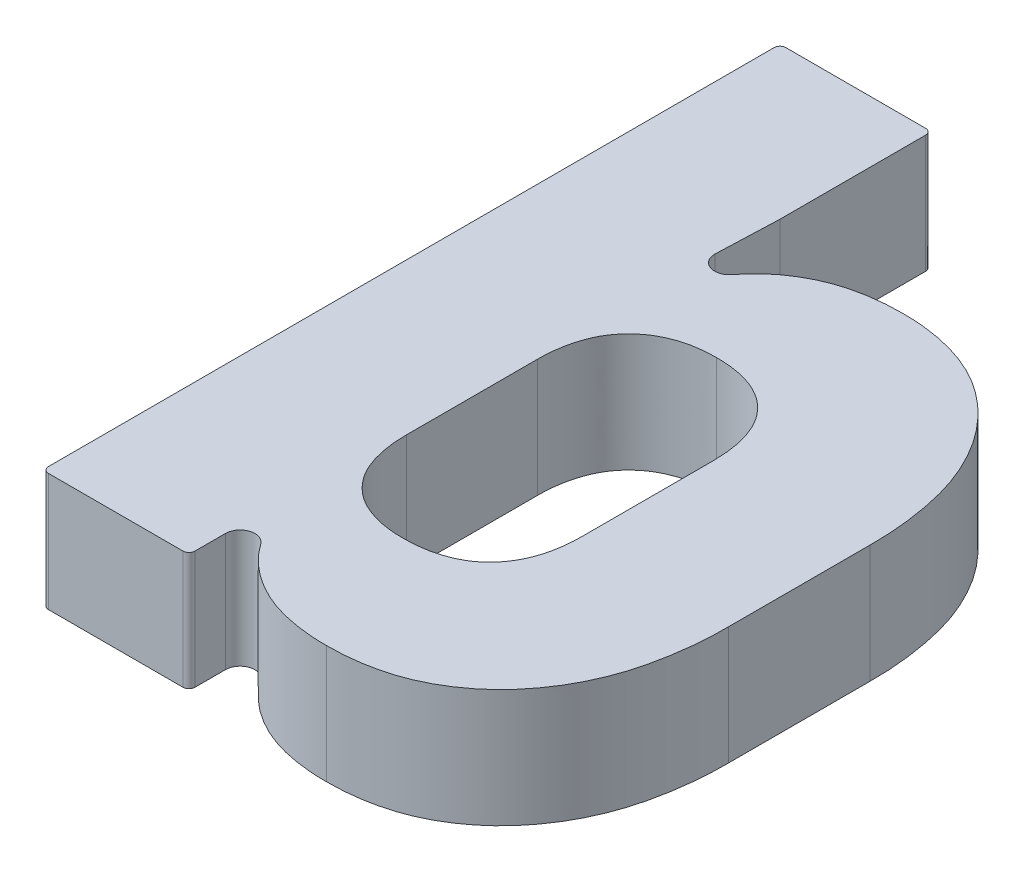
SolidWorks part; units mm, degrees
ref_plane "Front Plane" through (0, 0, 0) normal (0, 0, 1) x (1, 0, 0)
ref_plane "Top Plane" through (0, 0, 0) normal (0, 1, 0) x (1, 0, 0)
ref_plane "Right Plane" through (0, 0, 0) normal (1, 0, 0) x (0, 0, -1)
sketch "Sketch1" plane through (0, 0, 0) normal (0, 1, 0) x (1, 0, 0)
  line L2 (36.1177, 19.9168) -> (36.1177, 0)
  line L3 (36.1177, 0) -> (11.2961, 0)
  line L4 (11.2961, 0) -> (11.2961, 125)
  line L5 (11.2961, 125) -> (36.9847, 125)
  line L6 (36.9847, 125) -> (36.9847, 99.3113)
  line L7 (36.9847, 99.3113) -> (36.1177, 76.199)
  line L10 (92.4495, 59.0815) -> (92.4495, 35.1021)
  line L11 (66.7856, 35.9691) -> (66.7856, 58.2144)
  line L12 (36.9847, 58.2144) -> (36.9847, 35.9691)
  spline S0 degree 3 poles (61.1375, -1.7093) (59.2964, -1.7263) (56.5951, -1.5145) (53.1297, -0.8168) (50.743, -0.0788) (48.524, 0.8997) (46.4557, 2.0674) (44.5312, 3.4383) (42.7707, 5.0197) (41.2152, 6.8114) (39.8415, 8.7587) (38.6541, 10.872) (37.2413, 14.5656) (36.5093, 17.6313) (36.1177, 19.9168) knots 0 0 0 0 0.15065 0.22105 0.289042 0.354731 0.419211 0.48318 0.547799 0.612474 0.676994 0.742654 0.810317 1 1 1 1
  spline S1 degree 3 poles (36.1177, 76.199) (37.079, 78.5138) (37.8217, 81.825) (39.8413, 85.4251) (41.2153, 87.372) (42.7706, 89.1639) (44.5312, 90.7452) (46.4557, 92.1161) (48.524, 93.2838) (50.743, 94.2623) (53.1297, 95.0003) (56.5951, 95.698) (59.2964, 95.9098) (61.1375, 95.8928) knots 0 0 0 0 0.21768 0.286848 0.354813 0.422943 0.491013 0.558398 0.626323 0.69552 0.767144 0.841304 1 1 1 1
  spline S2 degree 3 poles (61.1375, 95.8928) (63.3951, 95.9037) (66.7358, 95.6213) (70.9813, 94.5442) (73.936, 93.4517) (76.7059, 92.0301) (79.2899, 90.2803) (81.7146, 88.2364) (83.9267, 85.8824) (85.9422, 83.2868) (87.6702, 80.4423) (89.1706, 77.4064) (90.3909, 74.1471) (91.2891, 70.6632) (92.1999, 65.6448) (92.4801, 61.7415) (92.4495, 59.0815) knots 0 0 0 0 0.124488 0.183663 0.240987 0.297785 0.354849 0.412665 0.472231 0.532595 0.593488 0.655373 0.719037 0.784951 0.85343 1 1 1 1
  spline S3 degree 3 poles (92.4495, 35.1021) (92.4817, 32.4172) (92.2002, 28.4812) (91.2918, 23.4291) (90.3921, 19.9366) (89.1629, 16.6738) (87.685, 13.6255) (85.9322, 10.7958) (83.9353, 8.2026) (81.7126, 5.8731) (79.2902, 3.8513) (76.6987, 2.131) (73.9363, 0.7078) (70.985, -0.3925) (66.7284, -1.416) (63.398, -1.7319) (61.1375, -1.7093) knots 0 0 0 0 0.147807 0.216676 0.282534 0.346145 0.408386 0.46884 0.529153 0.58834 0.645814 0.702577 0.759327 0.816603 0.875617 1 1 1 1
  spline S4 degree 3 poles (51.8728, 20.5361) (54.0283, 20.5098) (57.1609, 20.948) (60.833, 22.6764) (63.0085, 24.4821) (64.7164, 26.7603) (66.4249, 30.5381) (66.7716, 33.7701) (66.7856, 35.9691) knots 0 0 0 0 0.26514 0.381315 0.494473 0.60893 0.728343 1 1 1 1
  spline S5 degree 3 poles (66.7856, 58.2144) (66.7718, 60.4068) (66.4178, 63.6257) (64.7238, 67.3956) (63.0004, 69.655) (60.8277, 71.4536) (57.1737, 73.2298) (54.0231, 73.6377) (51.8728, 73.6227) knots 0 0 0 0 0.271017 0.390595 0.504399 0.617713 0.734496 1 1 1 1
  spline S6 degree 3 poles (51.8728, 73.6227) (49.7597, 73.6442) (46.6592, 73.21) (43.0364, 71.4491) (40.8492, 69.6483) (39.0635, 67.4129) (37.3944, 63.6156) (36.9677, 60.4184) (36.9847, 58.2144) knots 0 0 0 0 0.261213 0.378316 0.492729 0.608095 0.728001 1 1 1 1
  spline S7 degree 3 poles (36.9847, 35.9691) (36.9676, 33.7584) (37.3874, 30.5481) (39.0709, 26.7431) (40.8411, 24.4887) (43.0312, 22.6809) (46.6718, 20.9674) (49.7547, 20.5037) (51.8728, 20.5361) knots 0 0 0 0 0.272641 0.392384 0.508393 0.622649 0.739144 1 1 1 1
  point P0 (36.2849, 75.966)
extrude "Boss-Extrude1" add sketch "Sketch1" against normal blind 20
fillet "Fillet1" radius 2.5 2 edges at (36.1177, -10, -76.199) (36.1177, -10, -19.9168)
fillet "Fillet2" radius 1 4 edges at (36.9847, -10, -125) (11.2961, -10, -125) (11.2961, -10, 0) (36.1177, -10, 0)
